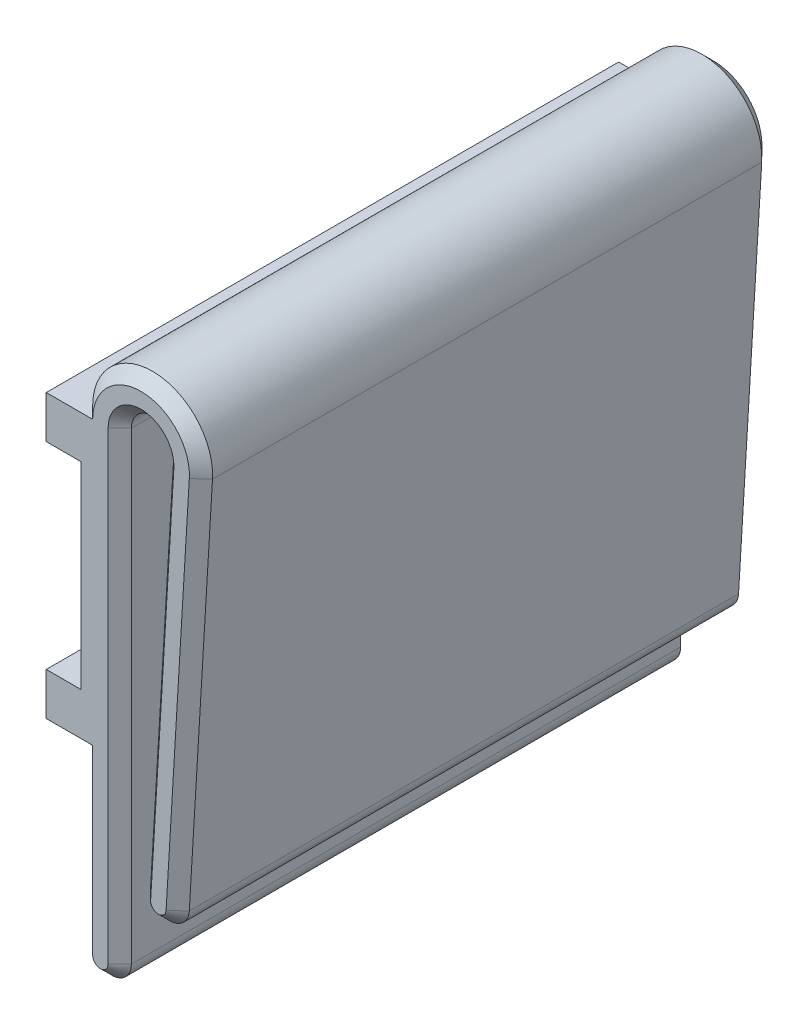
SolidWorks part; units mm, degrees
ref_plane "Front Plane" through (0, 0, 0) normal (0, 0, 1) x (1, 0, 0)
ref_plane "Top Plane" through (0, 0, 0) normal (0, 1, 0) x (1, 0, 0)
ref_plane "Right Plane" through (0, 0, 0) normal (1, 0, 0) x (0, 0, -1)
sketch "Sketch1" plane through (0, 0, 0) normal (0, 0, 1) x (1, 0, 0)
  line L0 (1.1, -0.0331) -> (0.5, -10)
  line L2 (0, 0) -> (0, -12)
  line L5 (2.0982, -0.0932) -> (1.4982, -10.0601)
  line L6 (-1, 0) -> (-1, -12)
  line L7 (-1, 0) -> (-1.9, 0)
  line L8 (-1.9, 0) -> (-1.9, -1.1)
  line L9 (-1.9, -1.1) -> (-1, -1.1)
  line L10 (-1, -6.2) -> (-1.9, -6.2)
  line L11 (-1.9, -6.2) -> (-1.9, -7.3)
  line L12 (-1.9, -7.3) -> (-1, -7.3)
  arc A0 (0, 0) -> (1.1, -0.0331) centre (0.5505, 0) cw
  arc A1 (-1, 0) -> (2.0982, -0.0932) centre (0.5505, 0) cw
  arc A2 (-1, -12) -> (0, -12) centre (-0.5, -12) ccw
  arc A3 (0.5, -10) -> (1.4982, -10.0601) centre (0.9991, -10.03) ccw
  dimension "D1" = 1.1
  dimension "D6" = 1.1
  dimension "D2" = 12
  dimension "D3" = 0.5
  dimension "D4" = 2
  dimension "D7" = 0.9
  dimension "D8" = 5.1
  dimension "D5" = 1
extrude "Boss-Extrude1" add sketch "Sketch1" along normal blind 14.8 contours L0 A3 L5 A1 L6 A2 L2 A0 | L8 L9 L6 L7 | L11 L12 L6 L10
chamfer "Chamfer1" distance 0.3 angle 45 16 edges at (-1, -9.65, 14.8) (-1, -9.65, 0) (-0.5, -12.5, 0) (-0.5, -12.5, 14.8) (0, -6, 0) (0, -6, 14.8) (0.567, 0.5502, 0) (0.567, 0.5502, 14.8) (0.8, -5.0165, 0) (0.8, -5.0165, 14.8) (0.5971, 1.5498, 0) (0.5971, 1.5498, 14.8) (0.9691, -10.5291, 0) (0.9691, -10.5291, 14.8) (1.7982, -5.0766, 0) (1.7982, -5.0766, 14.8)
